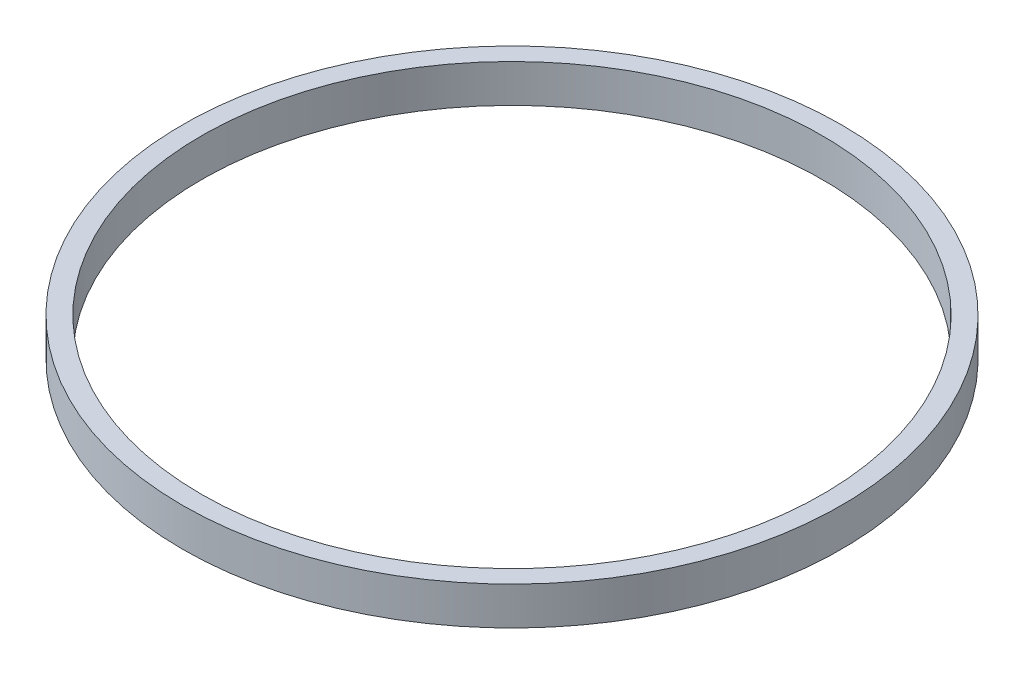
SolidWorks part; units mm, degrees
ref_plane "Спереди" through (0, 0, 0) normal (0, 0, 1) x (1, 0, 0)
ref_plane "Сверху" through (0, 0, 0) normal (0, 1, 0) x (1, 0, 0)
ref_plane "Справа" through (0, 0, 0) normal (1, 0, 0) x (0, 0, -1)
sketch "Эскиз1" plane through (0, 0, 0) normal (0, 1, 0) x (1, 0, 0)
  circle A0 centre (0, 0) radius 26
  circle A1 centre (0, 0) radius 24.5
  dimension "D1" = 52
  dimension "D2" = 49
extrude "Бобышка-Вытянуть1" add sketch "Эскиз1" along normal blind 3
